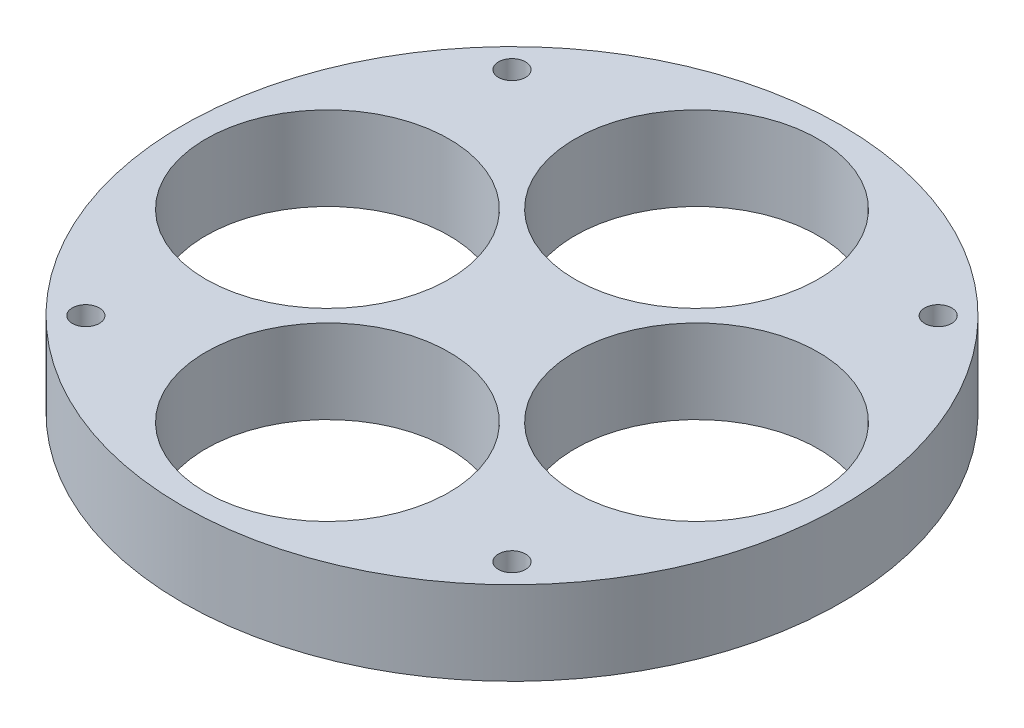
SolidWorks part; units mm, degrees
ref_plane "Front Plane" through (0, 0, 0) normal (0, 0, 1) x (1, 0, 0)
ref_plane "Top Plane" through (0, 0, 0) normal (0, 1, 0) x (1, 0, 0)
ref_plane "Right Plane" through (0, 0, 0) normal (1, 0, 0) x (0, 0, -1)
sketch "Sketch1" plane through (0, 0, 0) normal (0, 1, 0) x (1, 0, 0)
  line L0 (0, 0) -> (16.1645, 16.1645)
  line L1 (0, 0) -> (14, 0)
  circle A0 centre (0, 0) radius 25
  circle A1 centre (16.1645, 16.1645) radius 1.025
  circle A2 centre (16.1645, -16.1645) radius 1.025
  circle A3 centre (-16.1645, -16.1645) radius 1.025
  circle A4 centre (-16.1645, 16.1645) radius 1.025
  circle A5 centre (14, 0) radius 9.225
  circle A6 centre (0, -14) radius 9.225
  circle A7 centre (-14, 0) radius 9.225
  circle A8 centre (0, 14) radius 9.225
  point P14 (0, 0)
  point P23 (0, 0)
  dimension "D1" = 50
  dimension "D3" = 2.05
  dimension "D6" = 18.45
  dimension "D2" = 22.86
  dimension "D5" = 14
  dimension "D4" = 4
  dimension "D7" = 4
extrude "Boss-Extrude1" add sketch "Sketch1" along normal blind 6.35
